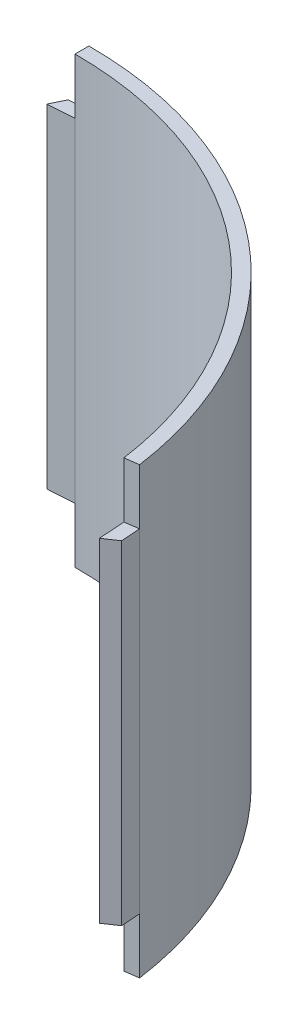
SolidWorks part; units mm, degrees
ref_plane "前视基准面" through (0, 0, 0) normal (0, 0, 1) x (1, 0, 0)
ref_plane "上视基准面" through (0, 0, 0) normal (0, 1, 0) x (1, 0, 0)
ref_plane "右视基准面" through (0, 0, 0) normal (1, 0, 0) x (0, 0, -1)
sketch "草图1" plane through (0, 0, 0) normal (0, 1, 0) x (1, 0, 0)
  line L0 (0, 705) -> (0, 0) construction
  line L1 (0, 0) -> (698.139, 98.117) construction
  line L2 (0, 705) -> (0, 680)
  line L3 (698.139, 98.117) -> (673.3823, 94.6377)
  arc A0 (0, 705) -> (698.139, 98.117) centre (0, 0) cw
  arc A1 (0, 680) -> (673.3823, 94.6377) centre (0, 0) cw
  dimension "D2" = 705
  dimension "D3" = 680
  dimension "D1" = 82
extrude "凸台-拉伸1" add sketch "草图1" along normal blind 800
ref_plane "基准面2" through (0, 400, 0) normal (0, 1, 0) x (1, 0, 0)
sketch "草图2" plane through (0, 400, 0) normal (0, 1, 0) x (1, 0, 0)
  line L0 (673.3823, 94.6377) -> (676.6911, 47.3189)
  line L2 (698.139, 98.117) -> (700.5651, 63.422)
  line L3 (676.6911, 47.3189) -> (700.5651, 63.422)
  line L4 (673.3823, 94.6377) -> (698.139, 98.117)
  line L5 (1595.1046, 111.5406) -> (1481.3826, 103.5884) construction
  dimension "D1" = 60
extrude "凸台-拉伸2" add sketch "草图2" against normal blind 300
ref_plane "基准面1" through (446.1201, 800, -513.2025) normal (-0.7547, 0, -0.6561) x (-0.6561, 0, 0.7547)
mirror "镜向1" about plane through (446.1201, 800, -513.2025) normal (-0.7547, 0, -0.6561) of "凸台-拉伸2"
mirror "镜向2" about plane through (0, 400, 0) normal (0, 1, 0) of "凸台-拉伸2"
mirror "镜向3" about plane through (446.1201, 800, -513.2025) normal (-0.7547, 0, -0.6561) of "镜向2"
